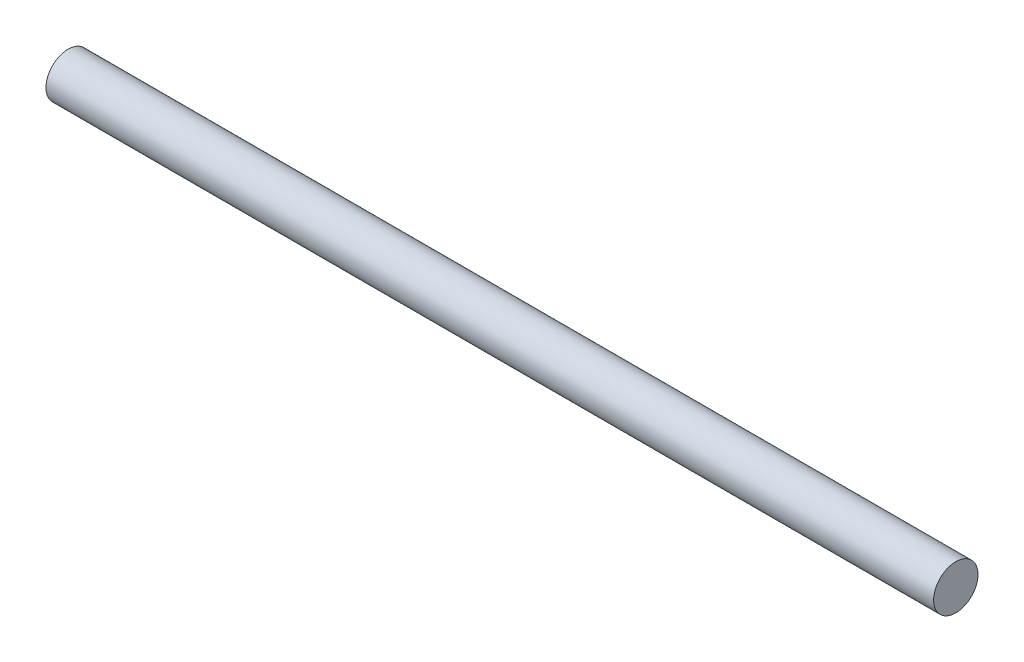
SolidWorks part; units mm, degrees
ref_plane "Front Plane" through (0, 0, 0) normal (0, 0, 1) x (1, 0, 0)
ref_plane "Top Plane" through (0, 0, 0) normal (0, 1, 0) x (1, 0, 0)
ref_plane "Right Plane" through (0, 0, 0) normal (1, 0, 0) x (0, 0, -1)
sketch "Sketch1" plane through (0, 0, 0) normal (1, 0, 0) x (0, 0, -1)
  circle A0 centre (0, 0) radius 3.175
extrude "Boss-Extrude1" add sketch "Sketch1" along normal mid plane 127
